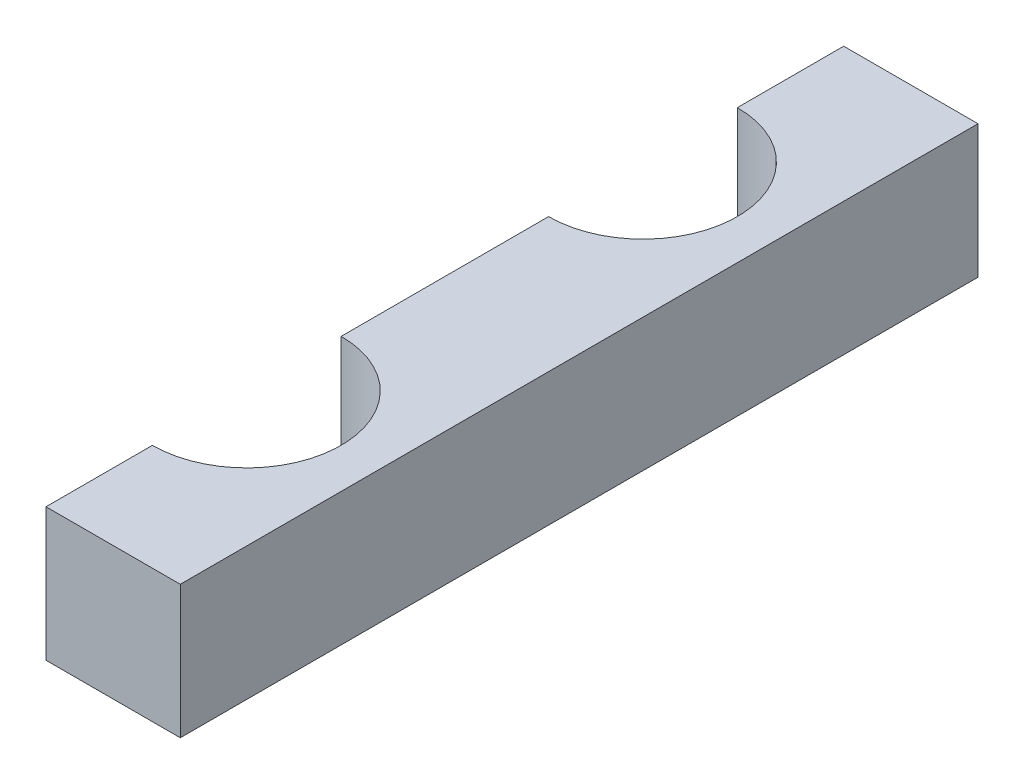
SolidWorks part; units mm, degrees
material "3.1355 (EN-AW 2024)"
ref_plane "Спереди" through (0, 0, 0) normal (0, 0, 1) x (1, 0, 0)
ref_plane "Сверху" through (0, 0, 0) normal (0, 1, 0) x (1, 0, 0)
ref_plane "Справа" through (0, 0, 0) normal (1, 0, 0) x (0, 0, -1)
sketch "Эскиз2" plane through (0, 382.6451, 0) normal (0, 1, 0) x (1, 0, 0)
  line L0 (3.5658, 110.7739) -> (3.5658, 50.7739) construction
  line L1 (-3.5342, 95.6739) -> (3.5658, 95.6739) construction
  line L2 (-3.5342, 65.8739) -> (3.5658, 65.8739) construction
  line L3 (3.5658, 102.7739) -> (3.5658, 110.7739)
  line L4 (3.5658, 88.5739) -> (3.5658, 72.9739)
  line L5 (3.5658, 58.7739) -> (3.5658, 50.7739)
  line L6 (10.6658, 95.6739) -> (13.6658, 95.6739) construction
  line L7 (3.5658, 110.7739) -> (13.6658, 110.7739)
  line L8 (13.6658, 110.7739) -> (13.6658, 50.7739)
  line L9 (3.5658, 50.7739) -> (13.6658, 50.7739)
  line L10 (-40.9296, 89.6601) -> (3.5658, 95.6739) construction
  arc A2 (3.5658, 102.7739) -> (3.5658, 88.5739) centre (3.5658, 95.6739) cw
  arc A3 (3.5658, 72.9739) -> (3.5658, 58.7739) centre (3.5658, 65.8739) cw
  dimension "D3" = 7.1
  dimension "D4" = 7.1
  dimension "D1" = 3
  dimension "D2" = 10.1
  dimension "D5" = 8
  dimension "D6" = 15.6
  dimension "D7" = 8
  dimension "D8" = 15.1
  dimension "D9" = 15.1
extrude "Бобышка-Вытянуть1" add sketch "Эскиз2" against normal blind 10
